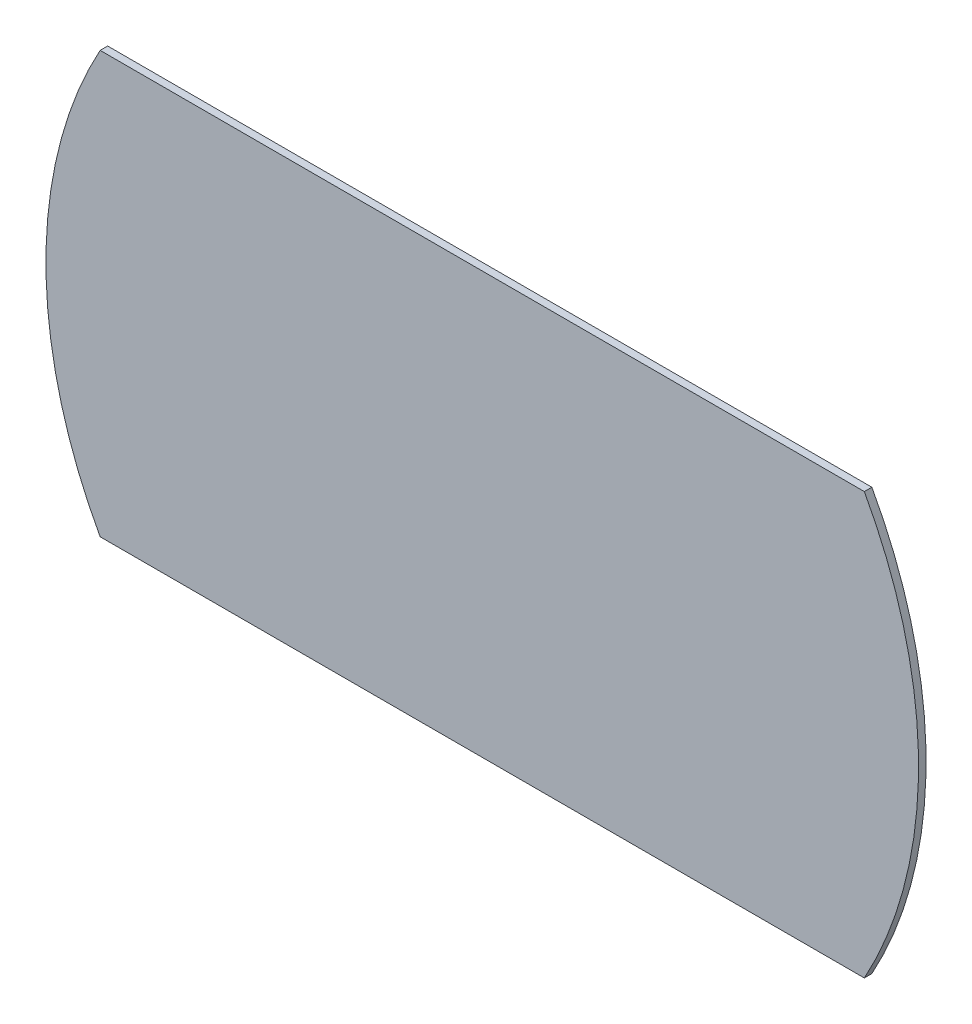
SolidWorks part; units mm, degrees
material "Стекло"
ref_plane "Спереди" through (0, 0, 0) normal (0, 0, 1) x (1, 0, 0)
ref_plane "Сверху" through (0, 0, 0) normal (0, 1, 0) x (1, 0, 0)
ref_plane "Справа" through (0, 0, 0) normal (1, 0, 0) x (0, 0, -1)
sketch "Эскиз1" plane through (0, 0, 0) normal (0, 0, 1) x (1, 0, 0)
  line L0 (-47.5065, 0) -> (37.9253, 0) construction
  line L1 (25.3969, 14) -> (-25.3969, 14)
  line L2 (25.3969, -14) -> (-25.3969, -14)
  arc A0 (-25.3969, 14) -> (-25.3969, -14) centre (0, 0) ccw
  arc A1 (25.3969, -14) -> (25.3969, 14) centre (0, 0) ccw
  dimension "D1" = 14
  dimension "D2" = 29
extrude "Бобышка-Вытянуть1" add sketch "Эскиз1" along normal blind 0.5
sketch "Эскиз2" plane through (0, 0, 0) normal (0, 0, -1) x (-1, 0, 0)
  line L4 (-24.4949, -12.5) -> (24.4949, -12.5)
  line L5 (24.4949, 12.5) -> (-24.4949, 12.5)
  line L6 (-24.4949, -12.5) -> (24.4949, -12.5)
  line L7 (24.4949, 12.5) -> (-24.4949, 12.5)
  arc A4 (-24.4949, 12.5) -> (-24.4949, -12.5) centre (0, 0) ccw
  arc A5 (24.4949, -12.5) -> (24.4949, 12.5) centre (0, 0) ccw
  arc A6 (-24.4949, 12.5) -> (-24.4949, -12.5) centre (0, 0) ccw
  arc A7 (24.4949, -12.5) -> (24.4949, 12.5) centre (0, 0) ccw
  dimension "D1" = 1.5
extrude "Бобышка-Вытянуть2" add sketch "Эскиз2" along normal blind 0.2
